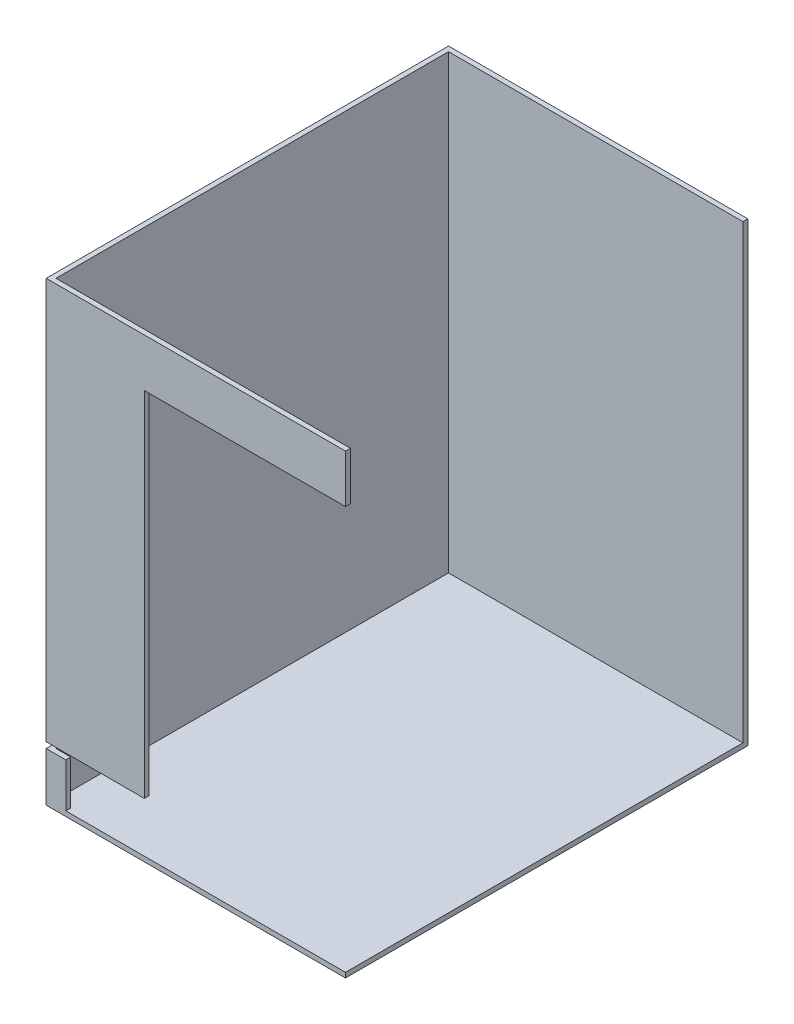
SolidWorks part; units mm, degrees
ref_plane "前视基准面" through (0, 0, 0) normal (0, 0, 1) x (1, 0, 0)
ref_plane "上视基准面" through (0, 0, 0) normal (0, 1, 0) x (1, 0, 0)
ref_plane "右视基准面" through (0, 0, 0) normal (1, 0, 0) x (0, 0, -1)
other "Configuration Table"
sketch "草图1" plane through (0, 0, 0) normal (0, 1, 0) x (1, 0, 0)
  line L1 (0, 0) -> (150, 0)
  line L2 (0, 0) -> (0, -200)
  line L3 (0, -200) -> (150, -200)
  line L4 (150, 0) -> (150, -200)
  dimension "D1" = 150
  dimension "D2" = 200
extrude "凸台-拉伸1" add sketch "草图1" along normal blind 230
shell "抽壳1" thickness 2.5
sketch "草图2" plane through (0, 0, 202.5) normal (0, 0, 1) x (1, 0, 0)
  line L0 (-2.5, 230) -> (-2.5, -2.5) construction
  line L1 (150, 230) -> (150, -2.5) construction
  line L2 (-2.5, 25.5) -> (47.5, 25.5)
  line L5 (150, 30.5) -> (150, 27.5)
  line L6 (47.5, 25.5) -> (47.5, 205.5)
  line L7 (47.5, 205.5) -> (150, 205.5)
  line L8 (150, 205.5) -> (150, 30.5)
  line L9 (-2.5, 22.5) -> (150, 22.5)
  line L10 (150, 22.5) -> (150, 27.5)
  line L11 (-2.5, 25.5) -> (-2.5, 22.5)
  point P0 (-2.5, 22.5)
  point P1 (-2.5, 25.5)
  point P11 (47.5, 25.5)
  dimension "D1" = 25
  dimension "D2" = 3
  dimension "D3" = 50
extrude "切除-拉伸1" cut sketch "草图2" against normal blind 3
sketch "草图6" plane through (0, 0, 202.5) normal (0, 0, 1) x (1, 0, 0)
  line L0 (-2.5, 22.5) -> (150, 22.5) construction
  line L1 (7.5, 22.5) -> (150, 22.5)
  line L2 (7.5, 22.5) -> (7.5, 0)
  line L3 (7.5, 0) -> (150, 0)
  line L4 (150, 22.5) -> (150, 0)
  dimension "D1" = 10
extrude "切除-拉伸2" cut sketch "草图6" against normal blind 30
ref_plane "基准面1" through (0, 0, 0) normal (1, 0, 0) x (0, 0, -1)
ref_plane "基准面2" through (0, -2.5, 0) normal (0, -1, 0) x (-1, 0, 0)
